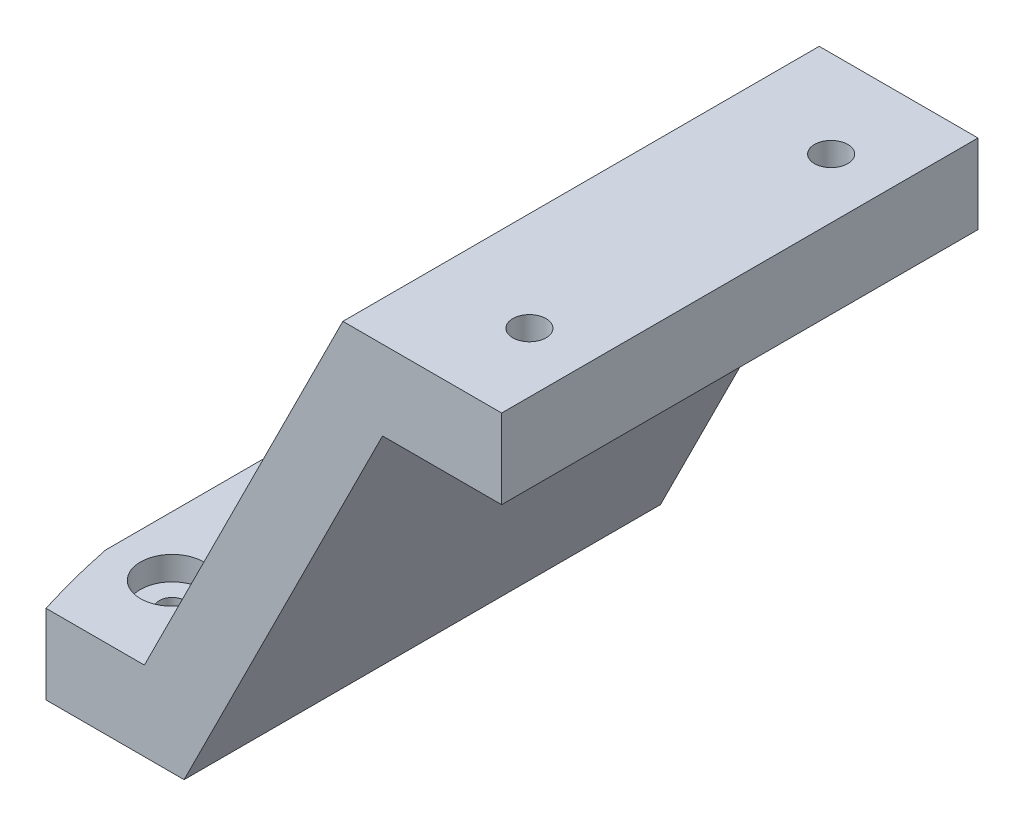
SolidWorks part; units mm, degrees
ref_plane "前视基准面" through (0, 0, 0) normal (0, 0, 1) x (1, 0, 0)
ref_plane "上视基准面" through (0, 0, 0) normal (0, 1, 0) x (1, 0, 0)
ref_plane "右视基准面" through (0, 0, 0) normal (1, 0, 0) x (0, 0, -1)
sketch "草图1" plane through (0, 0, 0) normal (0, 0, 1) x (1, 0, 0)
  line L0 (0, 0) -> (-20, 0)
  line L1 (-20, 0) -> (-20, 10)
  line L2 (-20, 10) -> (-5, 10)
  line L3 (-5, 10) -> (20, 60)
  line L4 (20, 60) -> (40, 60)
  line L5 (40, 60) -> (40, 50)
  line L6 (40, 50) -> (25, 50)
  line L7 (25, 50) -> (0, 0)
  dimension "D1" = 10
  dimension "D2" = 10
  dimension "D3" = 60
  dimension "D4" = 20
  dimension "D5" = 20
  dimension "D6" = 20
  dimension "D7" = 15
extrude "凸台-拉伸1" add sketch "草图1" along normal blind 60
sketch "草图2" plane through (0, 10, 0) normal (0, 1, 0) x (1, 0, 0)
  line L0 (78, -30) -> (20, -30) construction
  line L1 (20, -60) -> (20, 0) construction
  circle A0 centre (78, -30) radius 100
  circle A1 centre (78, -30) radius 171.9768
  dimension "D1" = 200
  dimension "D3" = 343.9535
  dimension "D2" = 58
extrude "切除-拉伸1" cut sketch "草图2" against normal blind 60
sketch "草图3" plane through (-8, 4, 0) normal (-0.8944, 0.4472, 0) x (0, 0, 1)
  line L0 (30, 34.6591) -> (60, 34.6591) construction
  line L1 (10, 14.6591) -> (50, 14.6591)
  line L2 (10, 14.6591) -> (10, 54.6591)
  line L3 (10, 54.6591) -> (50, 54.6591)
  line L4 (50, 14.6591) -> (50, 54.6591)
  line L5 (10, 14.6591) -> (50, 54.6591) construction
  line L6 (10, 54.6591) -> (50, 14.6591) construction
  line L7 (60, 62.6099) -> (60, 6.7082) construction
  line L8 (30, 34.6591) -> (30, 6.7082) construction
  line L9 (60, 6.7082) -> (0, 6.7082) construction
  point P0 (30, 34.6591)
  dimension "D1" = 40
  dimension "D2" = 40
extrude "切除-拉伸2" cut sketch "草图3" against normal blind 5
fillet "圆角1" radius 5 4 edges at (0.7918, 15.9934, 50) (0.7918, 15.9934, 10) (18.6803, 51.7705, 50) (18.6803, 51.7705, 10)
sketch "草图4" plane through (0, 10, 0) normal (0, 1, 0) x (1, 0, 0)
  line L0 (-12.5, -49) -> (-12.5, -11) construction
  line L1 (-20, -30) -> (-5, -30) construction
  line L2 (-20, -49.8997) -> (-20, -10.1003) construction
  line L3 (-5, -60) -> (-5, 0) construction
  circle A0 centre (-12.5, -49) radius 1.6
  circle A1 centre (-12.5, -11) radius 1.6
  point P8 (-12.5, -30)
  point P9 (-12.5, -30)
  dimension "D2" = 3.2
  dimension "D3" = 3.2
  dimension "D1" = 38
extrude "切除-拉伸3" cut sketch "草图4" against normal blind 10
sketch "草图5" plane through (0, 10, 0) normal (0, 1, 0) x (1, 0, 0)
  circle A0 centre (-12.5, -49) radius 4
  circle A1 centre (-12.5, -11) radius 4
  dimension "D1" = 8
  dimension "D2" = 8
extrude "切除-拉伸4" cut sketch "草图5" against normal blind 3
sketch "草图6" plane through (0, 50, 0) normal (0, -1, 0) x (1, 0, 0)
  line L0 (32.5, 11) -> (32.5, 49) construction
  line L1 (40, 30) -> (25, 30) construction
  line L2 (40, 60) -> (40, 0) construction
  line L3 (25, 60) -> (25, 0) construction
  circle A0 centre (32.5, 11) radius 2.1
  circle A1 centre (32.5, 49) radius 2.1
  point P8 (32.5, 30)
  point P10 (32.5, 30)
  dimension "D2" = 4.2
  dimension "D3" = 4.2
  dimension "D1" = 38
extrude "切除-拉伸5" cut sketch "草图6" against normal through all
sketch "草图7" plane through (0, 50, 0) normal (0, -1, 0) x (1, 0, 0)
  line L1 (36.1, 14.6) -> (28.9, 14.6)
  line L2 (36.1, 14.6) -> (36.1, 7.4)
  line L3 (36.1, 7.4) -> (28.9, 7.4)
  line L4 (28.9, 14.6) -> (28.9, 7.4)
  line L5 (36.1, 14.6) -> (28.9, 7.4) construction
  line L6 (36.1, 7.4) -> (28.9, 14.6) construction
  line L7 (36.1, 52.6) -> (28.9, 52.6)
  line L8 (36.1, 52.6) -> (36.1, 45.4)
  line L9 (36.1, 45.4) -> (28.9, 45.4)
  line L10 (28.9, 52.6) -> (28.9, 45.4)
  line L11 (36.1, 52.6) -> (28.9, 45.4) construction
  line L12 (36.1, 45.4) -> (28.9, 52.6) construction
  point P0 (32.5, 11)
  point P6 (32.5, 49)
  dimension "D1" = 7.2
  dimension "D2" = 7.2
  dimension "D3" = 7.2
  dimension "D4" = 7.2
extrude "切除-拉伸6" cut sketch "草图7" against normal blind 3
